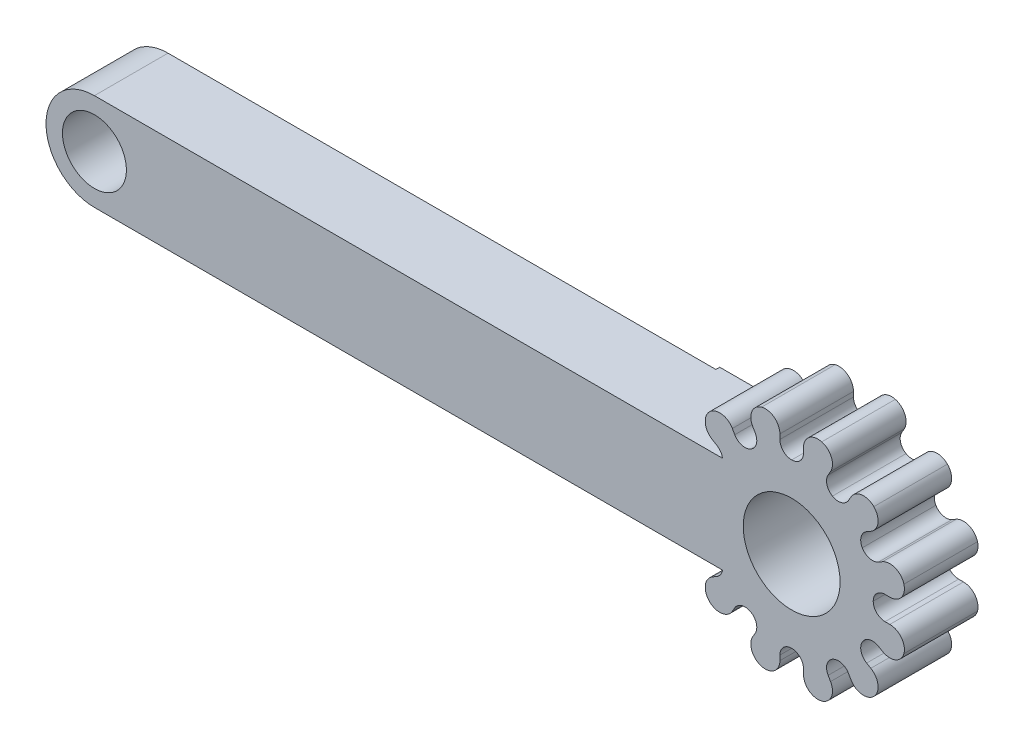
SolidWorks part; units mm, degrees
material "Anycubic PLA V3.0"
ref_plane "Front Plane" through (0, 0, 0) normal (0, 0, 1) x (1, 0, 0)
ref_plane "Top Plane" through (0, 0, 0) normal (0, 1, 0) x (1, 0, 0)
ref_plane "Right Plane" through (0, 0, 0) normal (1, 0, 0) x (0, 0, -1)
sketch "Sketch1" plane through (0, 0, 0) normal (0, 0, 1) x (1, 0, 0)
  line L0 (18, 0) -> (-18, 0) construction
  line L1 (-18, 2.5) -> (12.5456, 2.5)
  line L2 (-18, -2.5) -> (12.5456, -2.5)
  arc A0 (-18, 2.5) -> (-18, -2.5) centre (-18, 0) ccw
  circle A1 centre (-18, 0) radius 1.65
  arc A2 (12.5456, -2.5) -> (12.5456, 2.5) centre (18, 0) ccw
  point P4 (0, 0)
  dimension "D2" = 12
  dimension "D3" = 3.3
  dimension "D4" = 5
  dimension "D1" = 36
extrude "Boss-Extrude1" add sketch "Sketch1" along normal blind 3.8
sketch "Sketch2" plane through (0, 0, 3.8) normal (0, 0, 1) x (1, 0, 0)
  line L0 (18, 6) -> (18, -6) construction
  line L1 (18, 0) -> (22.2426, 4.2426) construction
  line L2 (18, 0) -> (19.5529, 5.7956) construction
  line L4 (18, 0) -> (20.105, 3.646) construction
  line L6 (20.0081, 4.6956) -> (19.8829, 4.4792)
  line L7 (21.0624, 4.0868) -> (20.9376, 3.8702)
  arc A0 (19.5529, 5.7956) -> (22.2426, 4.2426) centre (19.724, 2.9861) cw
  arc A8 (12.5456, -2.5) -> (12.5456, 2.5) centre (18, 0) ccw construction
  arc A9 (19.5529, 5.7956) -> (20.0081, 4.6956) centre (19.3589, 5.0711) cw
  arc A10 (19.8829, 4.4792) -> (20.105, 3.646) centre (20.4109, 4.1737) ccw
  arc A11 (20.9376, 3.8702) -> (20.105, 3.646) centre (20.4091, 4.1748) cw
  arc A12 (22.2426, 4.2426) -> (21.0624, 4.0868) centre (21.7123, 3.7124) ccw
  dimension "D4" = 15
  dimension "D6" = 1.1
  dimension "D7" = 0.25
  dimension "D5" = 0.75
  dimension "D8" = 0.61
  dimension "D1" = 15
  dimension "D2" = 30
  dimension "D3" = 4.21
extrude "Cut-Extrude1" cut sketch "Sketch2" against normal through all
pattern_circular "CirPattern1" count 12 over 360 about axis through (18, 0, 0) along (0, 0, 1) of "Cut-Extrude1"
sketch "Sketch3" plane through (0, 0, 3.8) normal (0, 0, 1) x (1, 0, 0)
  line L0 (12.3083, 2.5) -> (-18, 2.5) construction
  line L1 (10.2871, 2.5) -> (16.2777, 2.5)
  line L2 (10.2871, 2.5) -> (10.2871, -2.5)
  line L3 (10.2871, -2.5) -> (16.2777, -2.5)
  line L4 (16.2777, 2.5) -> (16.2777, -2.5)
  line L5 (-18, -2.5) -> (12.3083, -2.5) construction
extrude "Boss-Extrude2" add sketch "Sketch3" against normal blind 4
sketch "Sketch4" plane through (0, 0, 3.8) normal (0, 0, 1) x (1, 0, 0)
  line L0 (18, 6) -> (18, -6) construction
  circle A0 centre (18, 0) radius 2.5
  point P7 (18, 0)
  dimension "D1" = 5
extrude "Cut-Extrude2" cut sketch "Sketch4" against normal through all
